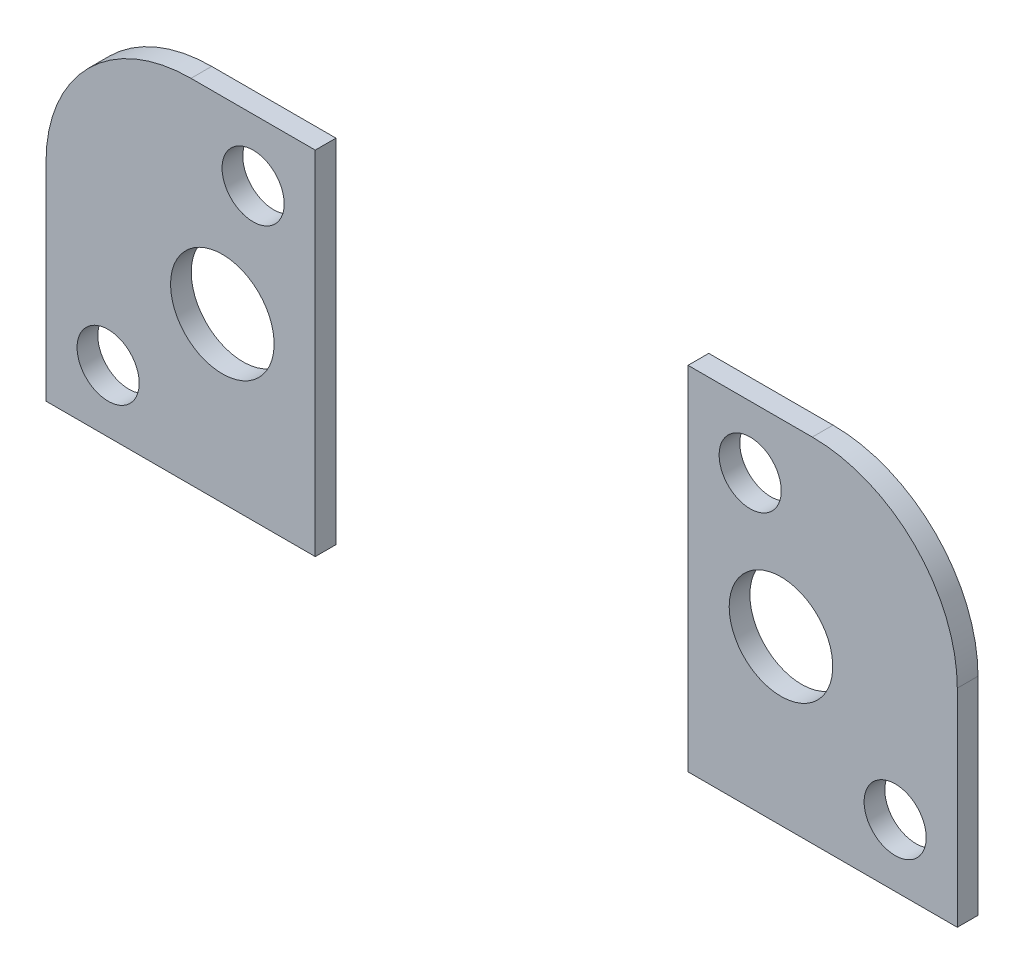
SolidWorks part; units mm, degrees
material "Thornel Mat VMA"
ref_plane "前视基准面" through (0, 0, 0) normal (0, 0, 1) x (1, 0, 0)
ref_plane "上视基准面" through (0, 0, 0) normal (0, 1, 0) x (1, 0, 0)
ref_plane "右视基准面" through (0, 0, 0) normal (1, 0, 0) x (0, 0, -1)
other "Configuration Table"
sketch "草图2" plane through (0, 0, 993.8097) normal (0, 0, -1) x (-1, 0, 0)
  line L0 (-9.3727, 7.3295) -> (-15.3727, 7.3295)
  line L2 (-22.3727, 0.3295) -> (-22.3727, -9.6705)
  line L3 (-22.3727, -9.6705) -> (-16.3727, -9.6705)
  line L4 (-16.3727, -9.6705) -> (-9.3727, -9.6705)
  line L5 (21.6273, -9.6705) -> (-22.3727, -9.6705) construction
  line L6 (-9.3727, -9.6705) -> (-9.3727, 7.3295)
  line L7 (8.6273, 7.3295) -> (8.6273, -9.6705)
  line L8 (8.6273, -9.6705) -> (21.6273, -9.6705)
  line L9 (21.6273, -9.6705) -> (21.6273, 0.3295)
  line L11 (14.6273, 7.3295) -> (8.6273, 7.3295)
  arc A0 (-15.3727, 7.3295) -> (-22.3727, 0.3295) centre (-15.3727, 0.3295) ccw
  circle A1 centre (-13.8593, -1.7705) radius 2.5
  arc A2 (21.6273, 0.3295) -> (14.6273, 7.3295) centre (14.6273, 0.3295) ccw
  circle A3 centre (13.114, -1.7705) radius 2.5
  circle A4 centre (-12.3727, 4.3295) radius 1.5
  circle A5 centre (-19.3727, -6.6705) radius 1.5
  circle A6 centre (11.6273, 4.3295) radius 1.5
  circle A7 centre (18.6273, -6.6705) radius 1.5
  dimension "D1" = 7
  dimension "D2" = 7
extrude "凸台-拉伸2" add sketch "草图2" along normal blind 1
